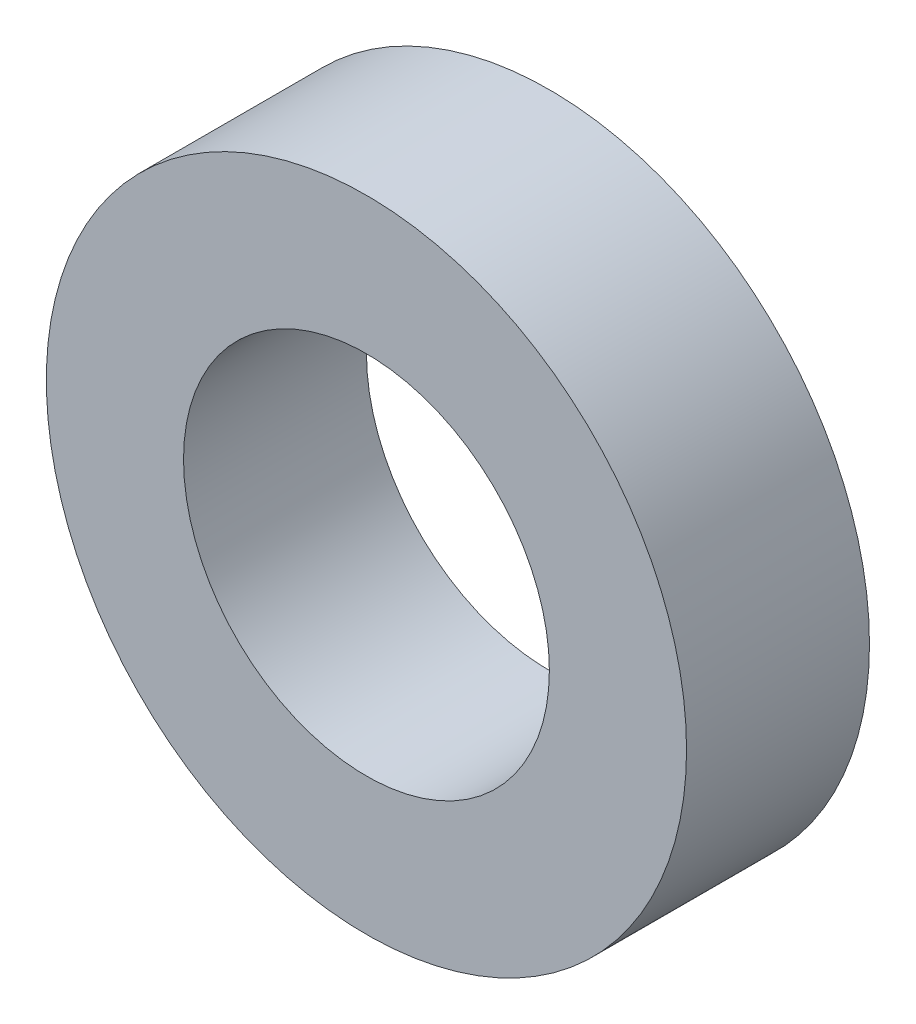
SolidWorks part; units mm, degrees
ref_plane "Front Plane" through (0, 0, 0) normal (0, 0, 1) x (1, 0, 0)
ref_plane "Top Plane" through (0, 0, 0) normal (0, 1, 0) x (1, 0, 0)
ref_plane "Right Plane" through (0, 0, 0) normal (1, 0, 0) x (0, 0, -1)
sketch "Sketch1" plane through (0, 0, 0) normal (0, 0, 1) x (1, 0, 0)
  line L0 (0, -5.5263) -> (0, -106.7984) construction
  line L5 (-87.2458, -40.0667) -> (88.0526, -40.0667) construction
  circle A4 centre (0.4034, -40.0667) radius 17.5
  circle A5 centre (0.4034, -40.0667) radius 10
  dimension "D9" = 20
  dimension "D10" = 35
extrude "Boss-Extrude1" add sketch "Sketch1" along normal blind 10
